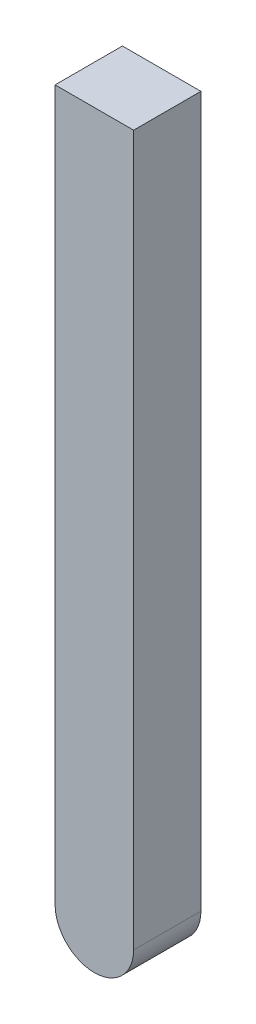
SolidWorks part; units mm, degrees
material "Cobre"
ref_plane "Plano frontal" through (0, 0, 0) normal (0, 0, 1) x (1, 0, 0)
ref_plane "Plano superior" through (0, 0, 0) normal (0, 1, 0) x (1, 0, 0)
ref_plane "Plano direito" through (0, 0, 0) normal (1, 0, 0) x (0, 0, -1)
sketch "Esboço1" plane through (0, 0, 0) normal (0, 0, 1) x (1, 0, 0)
  line L0 (-0.35, 3.165) -> (-0.35, -3.165)
  line L1 (0.35, -3.165) -> (0.35, 3.165)
  line L2 (0.35, 3.165) -> (-0.35, 3.165)
  line L3 (0, 3.165) -> (0, 0) construction
  line L4 (0, 0) -> (0.35, 0) construction
  arc A0 (-0.35, -3.165) -> (0.35, -3.165) centre (0, -3.165) ccw
  dimension "D1" = 0.7
  dimension "D2" = 6.33
extrude "Ressalto-extrusão1" add sketch "Esboço1" along normal mid plane 0.6
